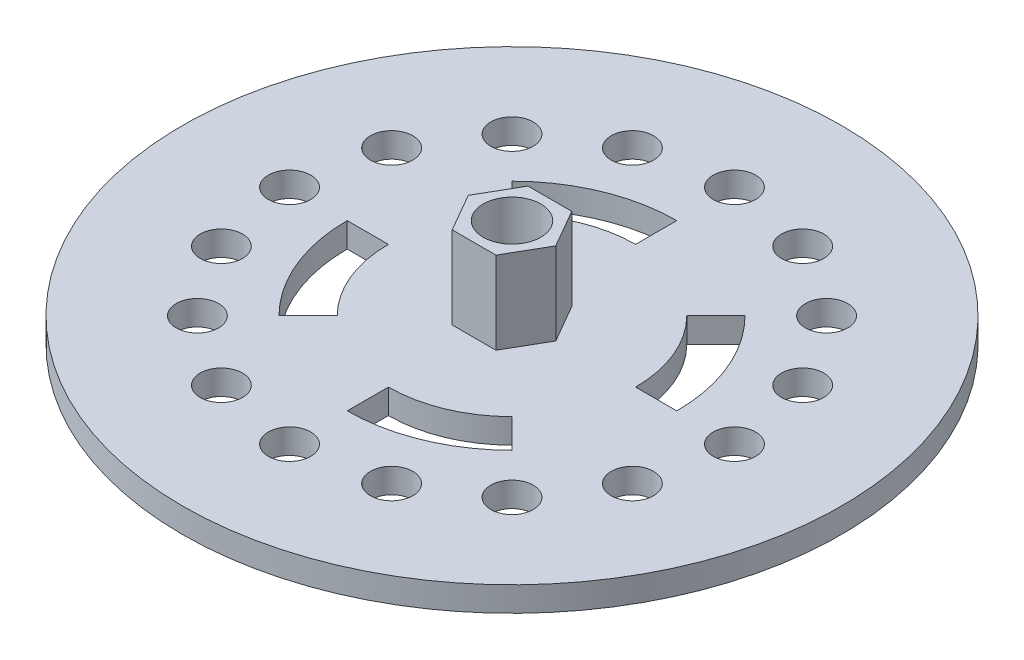
SolidWorks part; units mm, degrees
ref_plane "Front Plane" through (0, 0, 0) normal (0, 0, 1) x (1, 0, 0)
ref_plane "Top Plane" through (0, 0, 0) normal (0, 1, 0) x (1, 0, 0)
ref_plane "Right Plane" through (0, 0, 0) normal (1, 0, 0) x (0, 0, -1)
sketch "Sketch1" plane through (0, 0, 0) normal (0, 1, 0) x (1, 0, 0)
  circle A0 centre (0, 0) radius 50.8
  dimension "D1" = 101.6
extrude "Boss-Extrude1" add sketch "Sketch1" along normal blind 3.81
sketch "Sketch2" plane through (0, 3.81, 0) normal (0, 1, 0) x (1, 0, 0)
  line L0 (0, 0) -> (0, 25.4)
  line L1 (0, 0) -> (17.9605, 17.9605)
  line L2 (0, 0) -> (38.1, 0)
  line L3 (0, 0) -> (26.9408, -26.9408)
  line L4 (0, 0) -> (0, -38.1)
  line L5 (0, 0) -> (-26.9408, -26.9408)
  line L6 (0, 0) -> (-38.1, 0)
  line L7 (0, 0) -> (-26.9408, 26.9408)
  circle A0 centre (0, 0) radius 25.4
  circle A1 centre (0, 0) radius 19.05
  point P11 (-13.7464, 2.2911)
  dimension "D1" = 38.1
  dimension "D2" = 50.8
  dimension "D3" = 45
extrude "Cut-Extrude1" cut sketch "Sketch2" against normal through all contours A1 L0 A0 L7 | A1 L6 A0 L5 | A1 L4 A0 L3 | A1 L2 A0 L1
sketch "Sketch3" plane through (0, 3.81, 0) normal (0, 1, 0) x (1, 0, 0)
  line L0 (0, 0) -> (0, 25.4) construction
  line L1 (0, 0) -> (17.9605, 17.9605) construction
  line L2 (13.1222, 31.6798) -> (0, 0) construction
  circle A0 centre (13.1222, 31.6798) radius 3.2639
  circle A1 centre (24.2467, 24.2467) radius 3.2639
  circle A2 centre (31.6798, 13.1222) radius 3.2639
  circle A3 centre (34.29, 0) radius 3.2639
  circle A4 centre (31.6798, -13.1222) radius 3.2639
  circle A5 centre (24.2467, -24.2467) radius 3.2639
  circle A6 centre (13.1222, -31.6798) radius 3.2639
  circle A7 centre (0, -34.29) radius 3.2639
  circle A8 centre (-13.1222, -31.6798) radius 3.2639
  circle A9 centre (-24.2467, -24.2467) radius 3.2639
  circle A10 centre (-31.6798, -13.1222) radius 3.2639
  circle A11 centre (-34.29, 0) radius 3.2639
  circle A12 centre (-31.6798, 13.1222) radius 3.2639
  circle A13 centre (-24.2467, 24.2467) radius 3.2639
  circle A14 centre (-13.1222, 31.6798) radius 3.2639
  circle A15 centre (0, 34.29) radius 3.2639
  point P17 (0, 0)
  dimension "D1" = 6.5278
  dimension "D2" = 22.5
  dimension "D3" = 34.29
  dimension "D4" = 16
extrude "Cut-Extrude2" cut sketch "Sketch3" against normal through all contours A0 | A1 | A2 | A4 | A5 | A6 | A7 | A8 | A9 | A10 | A11 | A12 | A13 | A14 | A15 | A3
sketch "Sketch4" plane through (0, 3.81, 0) normal (0, 1, 0) x (1, 0, 0)
  line L0 (-3.3729, 5.842) -> (3.3729, 5.842)
  line L1 (3.3729, 5.842) -> (6.7458, 0)
  line L2 (6.7458, 0) -> (3.3729, -5.842)
  line L3 (3.3729, -5.842) -> (-3.3729, -5.842)
  line L4 (-3.3729, -5.842) -> (-6.7458, 0)
  line L5 (-6.7458, 0) -> (-3.3729, 5.842)
  circle A0 centre (0, 0) radius 4.445
  point P6 (0, 5.842)
  dimension "D3" = 8.89
  dimension "D1" = 120
  dimension "D2" = 11.684
extrude "Boss-Extrude2" add sketch "Sketch4" along normal blind 12.7 contours L5 L4 L3 L2 L1 L0 A0
